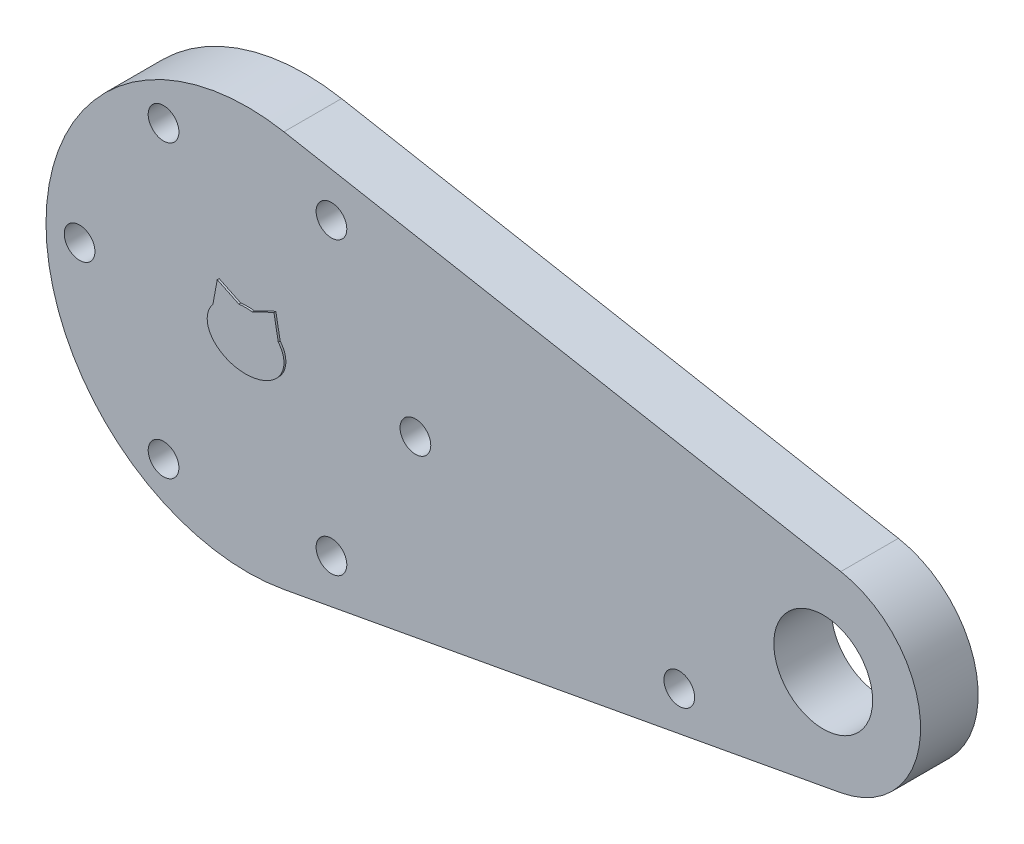
SolidWorks part; units mm, degrees
material "ABS"
ref_plane "前视基准面" through (0, 0, 0) normal (0, 0, 1) x (1, 0, 0)
ref_plane "上视基准面" through (0, 0, 0) normal (0, 1, 0) x (1, 0, 0)
ref_plane "右视基准面" through (0, 0, 0) normal (1, 0, 0) x (0, 0, -1)
other "Configuration Table"
sketch "草图1" plane through (0, 0, 0) normal (0, 0, 1) x (1, 0, 0)
  line L0 (60, 0) -> (0, 0) construction
  line L1 (61.8355, -9.9827) -> (3.7975, -20.6538)
  line L2 (3.7975, 20.6538) -> (61.8355, 9.9827)
  arc A0 (3.7975, 20.6538) -> (3.7975, -20.6538) centre (0, 0) ccw
  circle A1 centre (60, 0) radius 5.15
  arc A2 (61.8355, -9.9827) -> (61.8355, 9.9827) centre (60, 0) ccw
  dimension "D2" = 42
  dimension "D3" = 10.3
  dimension "D4" = 5
  dimension "D1" = 60
extrude "凸台-拉伸1" add sketch "草图1" along normal blind 6
sketch "草图3" plane through (0, 0, 6) normal (0, 0, 1) x (1, 0, 0)
  line L0 (0, 0) -> (69.2927, 0) construction
  line L1 (0, 0) -> (8.75, 15.1554) construction
  circle A0 centre (0, 0) radius 17.5 construction
  circle A1 centre (8.75, 15.1554) radius 1.6
  circle A2 centre (17.5, 0) radius 1.6
  circle A3 centre (8.75, -15.1554) radius 1.6
  circle A4 centre (-8.75, -15.1554) radius 1.6
  circle A5 centre (-17.5, 0) radius 1.6
  circle A6 centre (-8.75, 15.1554) radius 1.6
  dimension "D1" = 35
  dimension "D3" = 3.2
  dimension "D2" = 60
extrude "切除-拉伸2" cut sketch "草图3" against normal through all
sketch "草图5" plane through (0, 0, 0) normal (0, 0, -1) x (-1, 0, 0)
  circle A0 centre (0, 0) radius 13.5
  dimension "D1" = 27
extrude "凸台-拉伸3" add sketch "草图5" along normal blind 0.5
sketch "草图4" plane through (0, 0, -0.5) normal (0, 0, -1) x (-1, 0, 0)
  circle A0 centre (0, 0) radius 12.35
  circle A1 centre (0, 0) radius 7.65
  arc A2 (-3.7975, -20.6538) -> (-3.7975, 20.6538) centre (0, 0) ccw construction
  dimension "D1" = 24.7
  dimension "D2" = 15.3
extrude "凸台-拉伸2" add sketch "草图4" along normal blind 4
sketch "草图6" plane through (0, 0, -0.5) normal (0, 0, -1) x (-1, 0, 0)
  circle A0 centre (0, 0) radius 3
  dimension "D1" = 6
extrude "切除-拉伸3" cut sketch "草图6" against normal blind 3
sketch "草图7" plane through (0, 0, 0) normal (0, 0, -1) x (-1, 0, 0)
  circle A0 centre (8.75, 15.1554) radius 2.85
  circle A1 centre (17.5, 0) radius 2.85
  circle A2 centre (8.75, -15.1554) radius 2.85
  circle A3 centre (-8.75, -15.1554) radius 2.85
  circle A4 centre (-17.5, 0) radius 2.85
  circle A5 centre (-8.75, 15.1554) radius 2.85
  point P16 (0, 0)
  dimension "D1" = 5.7
  dimension "D2" = 6
extrude "切除-拉伸4" cut sketch "草图7" against normal blind 3
sketch "草图9" plane through (0, 0, 6) normal (0, 0, 1) x (1, 0, 0)
  line L0 (0, -3) -> (0, 5.908) construction
  line L1 (-2.9548, 4.0335) -> (-3.4049, 1.5744)
  line L2 (-2.9548, 4.0335) -> (-0.7, 2.9537)
  line L3 (2.9548, 4.0335) -> (0.7, 2.9537)
  line L4 (2.9548, 4.0335) -> (3.4049, 1.5744)
  ellipse E0 centre (0, 0) end of major axis (4, 0) minor radius 3 (-3.4049, 1.5744) -> (3.4049, 1.5744) ccw
  ellipse E1 centre (0, 0) end of major axis (4, 0) minor radius 3 (0.7, 2.9537) -> (-0.7, 2.9537) ccw
  dimension "D1" = 8
  dimension "D2" = 6
  dimension "D3" = 2.5
  dimension "D4" = 2.5
  dimension "D5" = 5
  dimension "D6" = 0.7
extrude "凸台-拉伸4" add sketch "草图9" along normal blind 0.2
sketch "草图10" plane through (0, 0, 0) normal (0, 0, -1) x (-1, 0, 0)
  circle A0 centre (-45, -9) radius 1.6
  dimension "D3" = 3.2
  dimension "D1" = 9
  dimension "D2" = 45
extrude "切除-拉伸6" cut sketch "草图10" against normal through all
